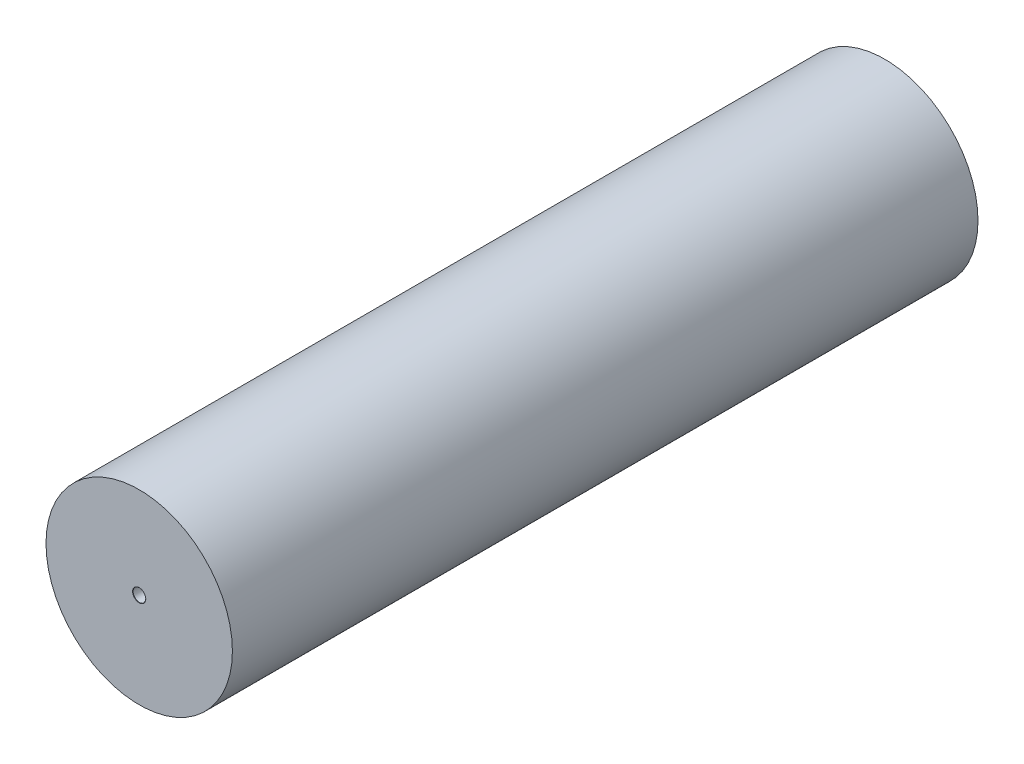
SolidWorks part; units mm, degrees
ref_plane "Front Plane" through (0, 0, 0) normal (0, 0, 1) x (1, 0, 0)
ref_plane "Top Plane" through (0, 0, 0) normal (0, 1, 0) x (1, 0, 0)
ref_plane "Right Plane" through (0, 0, 0) normal (1, 0, 0) x (0, 0, -1)
sketch "Sketch1" plane through (0, 0, 0) normal (0, 0, 1) x (1, 0, 0)
  circle A0 centre (0, 0) radius 127
  dimension "D1" = 254
extrude "Boss-Extrude1" add sketch "Sketch1" along normal blind 1016
hole_wizard "3/8 Rc Tapped Hole2" positions "Sketch5" profile "Sketch6" size "3/8" standard "BSI" end condition through all
sketch "Sketch5" plane through (0, 0, 1016) normal (0, 0, 1) x (1, 0, 0)
  point P0 (0, 2.3535)
sketch "Sketch6" plane through (0, 2.3535, 1016) normal (1, 0, 0) x (0, -1, 0)
  line L0 (0, 0) -> (0, 1016)
  line L1 (0, 1016) -> (25, 1016)
  line L3 (25, 1016) -> (25, 20.32)
  line L4 (25, 20.32) -> (7.9859, 20.32)
  line L5 (7.9859, 20.32) -> (8.6095, 0.3455)
  line L6 (8.6095, 0.3455) -> (8.955, 0)
  line L7 (8.955, 0) -> (0, 0)
  line L8 (0, -6.35) -> (0, 107.95) construction
  line L9 (-8.6095, 0.3455) -> (-8.955, 0) construction
  line L11 (-25, 20.32) -> (-7.9859, 20.32) construction
  line L12 (-7.9859, 20.32) -> (-8.6095, 0.3455) construction
  dimension "Thru Tap Drill Dia." = 50
  dimension "Thru Tap Drill Depth" = 1016
  dimension "Thread Dia." = 17.2189
  dimension "Thread Angle" = 3.576
  dimension "Thread Depth" = 20.32
  dimension "Near C'Sink Dia." = 17.91
  dimension "Near C'Sink Angle" = 90
